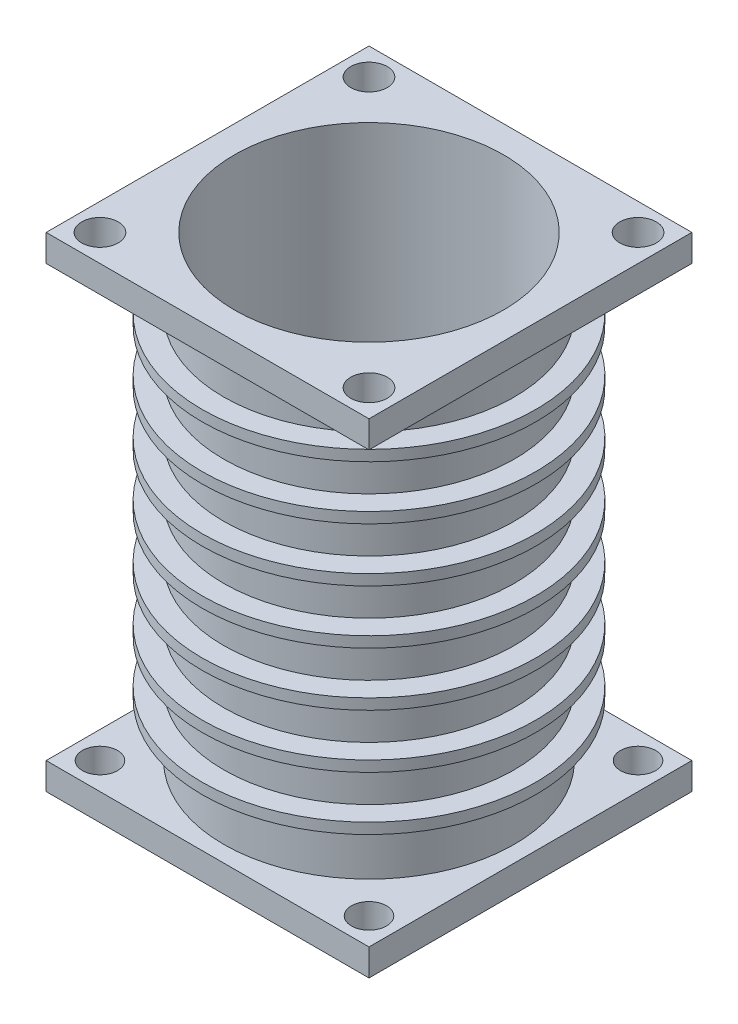
SolidWorks part; units mm, degrees
ref_plane "Front Plane" through (0, 0, 0) normal (0, 0, 1) x (1, 0, 0)
ref_plane "Top Plane" through (0, 0, 0) normal (0, 1, 0) x (1, 0, 0)
ref_plane "Right Plane" through (0, 0, 0) normal (1, 0, 0) x (0, 0, -1)
sketch "Sketch1" plane through (0, 0, 0) normal (0, 1, 0) x (1, 0, 0)
  line L0 (-15, -15) -> (-15, 15)
  line L1 (-12.5, -12.5) -> (12.5, -12.5)
  line L2 (-12.5, -12.5) -> (-12.5, 12.5)
  line L3 (-12.5, 12.5) -> (12.5, 12.5)
  line L4 (12.5, -12.5) -> (12.5, 12.5)
  line L5 (-12.5, -12.5) -> (12.5, 12.5) construction
  line L6 (-12.5, 12.5) -> (12.5, -12.5) construction
  line L7 (-15, 15) -> (15, 15)
  line L8 (15, -15) -> (15, 15)
  line L9 (-15, -15) -> (15, -15)
  circle A0 centre (-12.5, 12.5) radius 1.63
  circle A1 centre (12.5, 12.5) radius 1.63
  circle A2 centre (12.5, -12.5) radius 1.63
  circle A3 centre (-12.5, -12.5) radius 1.63
  point P0 (0, 0)
  dimension "D4" = 3.26
  dimension "D1" = 25
  dimension "D2" = 25
  dimension "D3" = 2.5
extrude "Boss-Extrude1" add sketch "Sketch1" along normal blind 2.5 contours A3 L1 A2 L4 A1 L3 A0 L2 | L0 L9 L8 L7 A3 L2 A0 L3 A1 L4 A2 L1
sketch "Sketch2" plane through (0, 2.5, 0) normal (0, 1, 0) x (1, 0, 0)
  circle A0 centre (0, 0) radius 12.5
  dimension "D1" = 25
extrude "Cut-Extrude1" cut sketch "Sketch2" against normal through all
sketch "Sketch3" plane through (0, 2.5, 0) normal (0, 1, 0) x (1, 0, 0)
  circle A2 centre (0, 0) radius 13.5
  circle A3 centre (0, 0) radius 13.5
  circle A4 centre (0, 0) radius 12.5
  circle A5 centre (0, 0) radius 12.5
  dimension "D1" = 1
  dimension "D2" = 0
extrude "Boss-Extrude2" add sketch "Sketch3" along normal blind 40
sketch "Sketch4" plane through (0, 42.5, 0) normal (0, 1, 0) x (1, 0, 0)
  circle A4 centre (0, 0) radius 15.5
  circle A5 centre (0, 0) radius 15.5
  dimension "D1" = 2
extrude "Boss-Extrude3" add sketch "Sketch4" along normal blind 1 from offset 5 offset against normal yes
pattern_linear "LPattern1" count 7 spacing 5 along (0, -1, 0) of "Boss-Extrude3"
sketch "Sketch5" plane through (0, 38.5, 0) normal (0, 1, 0) x (1, 0, 0)
  circle A0 centre (0, 0) radius 12.5
extrude "Cut-Extrude2" cut sketch "Sketch5" against normal through all and the other way blind 11
ref_plane "Plane1" [suppressed] through (0, 30, 0) normal (0, 1, 0) x (1, 0, 0)
mirror "Mirror1" [suppressed] about plane through (0, 30, 0) normal (0, 1, 0)
scale "Scale1" bodies to scale 107 scale about centroid uniform scaling yes scale factor 4
ref_plane "Plane2" through (0, 33.0745, 0) normal (0, 1, 0) x (1, 0, 0)
sketch "Sketch8" plane through (0, 113.0745, 0) normal (0, 1, 0) x (1, 0, 0)
  line L1 (-60, 60) -> (60, 60)
  line L2 (-60, 60) -> (-60, -60)
  line L3 (-60, -60) -> (60, -60)
  line L4 (60, 60) -> (60, -60)
extrude "Boss-Extrude5" add sketch "Sketch8" along normal blind 10
sketch "Sketch9" plane through (0, 123.0745, 0) normal (0, 1, 0) x (1, 0, 0)
  line L0 (0, 38.8695) -> (0, -35.2219) construction
  line L1 (-30.7764, 0) -> (29.4086, 0) construction
  line L2 (60, -60) -> (50, -60) construction
  line L3 (-60, -60) -> (60, -60) construction
  line L4 (50, -60) -> (50, -50) construction
  circle A0 centre (50, -50) radius 6.8
  circle A1 centre (-50, -50) radius 6.8
  circle A2 centre (-50, 50) radius 6.8
  circle A3 centre (50, 50) radius 6.8
extrude "Cut-Extrude3" cut sketch "Sketch9" against normal blind 10
sketch "Sketch10" plane through (0, -56.9255, 0) normal (0, -1, 0) x (1, 0, 0)
  circle A0 centre (0, 0) radius 50
extrude "Cut-Extrude4" cut sketch "Sketch10" against normal up to next
